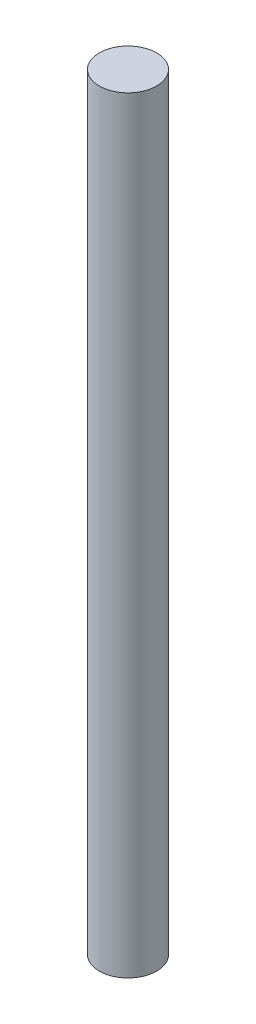
SolidWorks part; units mm, degrees
ref_plane "Front Plane" through (0, 0, 0) normal (0, 0, 1) x (1, 0, 0)
ref_plane "Top Plane" through (0, 0, 0) normal (0, 1, 0) x (1, 0, 0)
ref_plane "Right Plane" through (0, 0, 0) normal (1, 0, 0) x (0, 0, -1)
sketch "Sketch1" plane through (0, 0, 0) normal (0, 1, 0) x (1, 0, 0)
  circle A0 centre (0, 0) radius 1.385
  dimension "D1" = 2.77
extrude "Boss-Extrude1" add sketch "Sketch1" along normal blind 37
